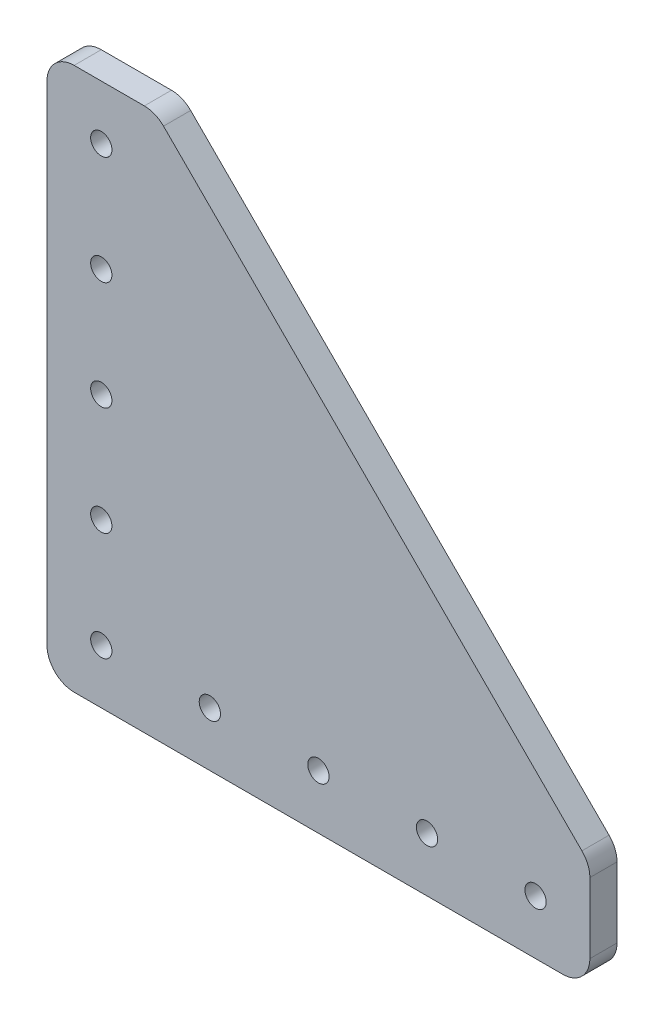
SolidWorks part; units mm, degrees
material "6061-T6 (SS)"
ref_plane "Front Plane" through (0, 0, 0) normal (0, 0, 1) x (1, 0, 0)
ref_plane "Top Plane" through (0, 0, 0) normal (0, 1, 0) x (1, 0, 0)
ref_plane "Right Plane" through (0, 0, 0) normal (1, 0, 0) x (0, 0, -1)
sketch "Sketch1" plane through (0, 0, 0) normal (0, 0, 1) x (1, 0, 0)
  line L0 (0, 0) -> (0, 127)
  line L1 (0, 127) -> (25.4, 127)
  line L2 (25.4, 127) -> (25.4, 25.4)
  line L3 (25.4, 25.4) -> (127, 25.4)
  line L4 (127, 25.4) -> (127, 0)
  line L5 (127, 0) -> (0, 0)
  line L6 (25.4, 127) -> (127, 25.4)
  circle A0 centre (12.7, 12.7) radius 2.4892
  circle A1 centre (38.1, 12.7) radius 2.4892
  circle A2 centre (63.5, 12.7) radius 2.4892
  circle A3 centre (38.1, 38.1) radius 2.4892 construction
  circle A4 centre (63.5, 38.1) radius 2.4892 construction
  circle A5 centre (38.1, 63.5) radius 2.4892 construction
  circle A6 centre (63.5, 63.5) radius 2.4892 construction
  circle A7 centre (38.1, 88.9) radius 2.4892 construction
  circle A8 centre (63.5, 88.9) radius 2.4892 construction
  circle A9 centre (12.7, 38.1) radius 2.4892
  circle A10 centre (12.7, 63.5) radius 2.4892
  circle A11 centre (12.7, 88.9) radius 2.4892
  circle A12 centre (12.7, 114.3) radius 2.4892
  circle A13 centre (38.1, 114.3) radius 2.4892 construction
  circle A14 centre (63.5, 114.3) radius 2.4892 construction
  circle A21 centre (88.9, 12.7) radius 2.4892
  circle A22 centre (114.3, 12.7) radius 2.4892
  circle A24 centre (88.9, 38.1) radius 2.4892 construction
  circle A25 centre (114.3, 38.1) radius 2.4892 construction
  circle A27 centre (88.9, 63.5) radius 2.4892 construction
  circle A28 centre (114.3, 63.5) radius 2.4892 construction
  circle A30 centre (88.9, 88.9) radius 2.4892 construction
  circle A31 centre (114.3, 88.9) radius 2.4892 construction
  circle A33 centre (88.9, 114.3) radius 2.4892 construction
  circle A34 centre (114.3, 114.3) radius 2.4892 construction
  dimension "D2" = 4.9784
  dimension "D1" = 25.4
  dimension "D3" = 12.7
  dimension "D4" = 12.7
  dimension "D7" = 25.4
  dimension "D8" = 25.4
  dimension "D9" = 127
  dimension "D10" = 127
  dimension "D5" = 5
  dimension "D6" = 5
extrude "Boss-Extrude1" add sketch "Sketch1" along normal blind 6.35
fillet "Fillet1" radius 6.35 5 edges at (0, 0, 3.175) (0, 127, 3.175) (127, 0, 3.175) (25.4, 127, 3.175) (127, 25.4, 3.175)
